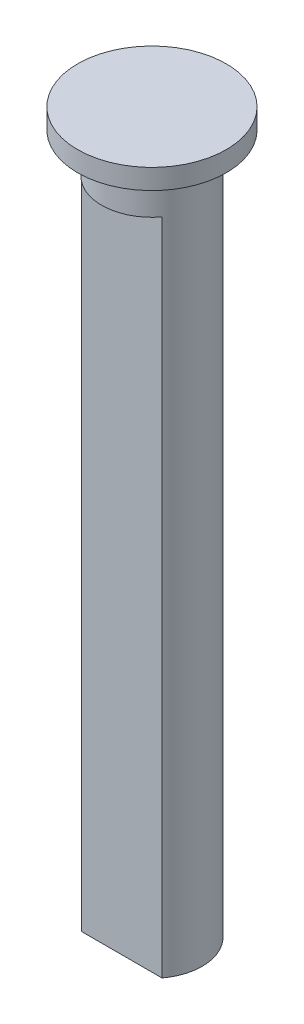
SolidWorks part; units mm, degrees
ref_plane "前视基准面" through (0, 0, 0) normal (0, 0, 1) x (1, 0, 0)
ref_plane "上视基准面" through (0, 0, 0) normal (0, 1, 0) x (1, 0, 0)
ref_plane "右视基准面" through (0, 0, 0) normal (1, 0, 0) x (0, 0, -1)
other "Configuration Table"
sketch "草图1" plane through (0, 0, 0) normal (0, 1, 0) x (1, 0, 0)
  line L0 (-2, -1.5) -> (2, -1.5)
  arc A0 (2, -1.5) -> (-2, -1.5) centre (0, 0) ccw
  dimension "D1" = 1.5
  dimension "D2" = 2.5
extrude "凸台-拉伸1" add sketch "草图1" along normal blind 27.8
sketch "草图2" plane through (0, 27.8, 0) normal (0, 1, 0) x (1, 0, 0)
  circle A0 centre (0, 0) radius 2.5
extrude "凸台-拉伸2" add sketch "草图2" along normal blind 2
sketch "草图3" plane through (0, 29.8, 0) normal (0, 1, 0) x (1, 0, 0)
  circle A0 centre (0, 0) radius 3.7
extrude "凸台-拉伸3" add sketch "草图3" along normal blind 1
sketch "草图4" plane through (0, 0, 0) normal (0, -1, 0) x (1, 0, 0)
  line L0 (-2, 1.5) -> (2, 1.5) construction
  line L1 (-2, 1.5) -> (2, 1.5)
  arc A0 (-2, 1.5) -> (2, 1.5) centre (0, 0) ccw
extrude "凸台-拉伸4" add sketch "草图4" along normal blind 2
sketch "草图5" plane through (0, -2, 0) normal (0, -1, 0) x (1, 0, 0)
  line L0 (-2, 1.5) -> (2, 1.5)
  arc A0 (-2, 1.5) -> (2, 1.5) centre (0, 0) ccw
  dimension "D1" = 1.5
extrude "凸台-拉伸5" add sketch "草图5" along normal blind 3
